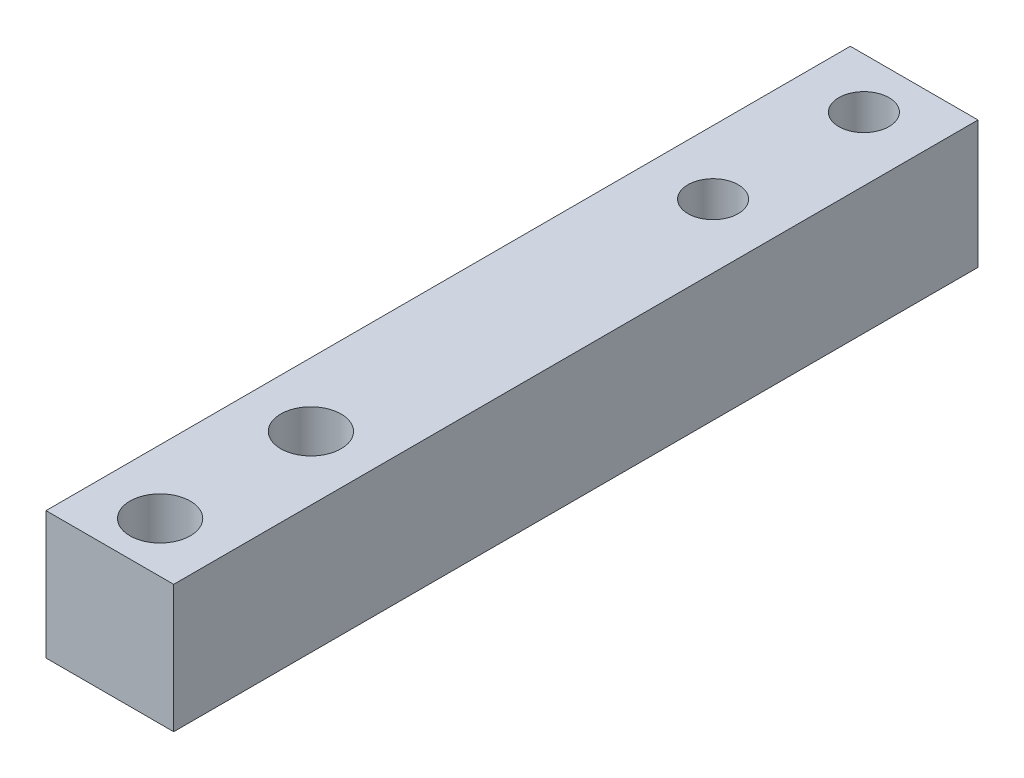
SolidWorks part; units mm, degrees
ref_plane "Front Plane" through (0, 0, 0) normal (0, 0, 1) x (1, 0, 0)
ref_plane "Top Plane" through (0, 0, 0) normal (0, 1, 0) x (1, 0, 0)
ref_plane "Right Plane" through (0, 0, 0) normal (1, 0, 0) x (0, 0, -1)
sketch "Sketch1" plane through (0, 0, 0) normal (0, 1, 0) x (1, 0, 0)
  line L0 (0, 40) -> (0, -40) construction
  line L1 (-6.35, 0) -> (6.35, 0) construction
  line L3 (-6.35, 40) -> (6.35, 40)
  line L4 (-6.35, 40) -> (-6.35, -40)
  line L5 (-6.35, -40) -> (6.35, -40)
  line L6 (6.35, 40) -> (6.35, -40)
  point P3 (0, 0)
  point P6 (0, 0)
  dimension "D1" = 80
  dimension "D2" = 12.7
extrude "Boss-Extrude1" add sketch "Sketch1" along normal blind 12.7
sketch "Sketch2" plane through (0, 12.7, 0) normal (0, 1, 0) x (1, 0, 0)
  line L0 (0, 40) -> (0, -40) construction
  circle A0 centre (0, 35) radius 2.5
  circle A1 centre (0, 20) radius 2.5
  circle A2 centre (0, -20) radius 3
  circle A3 centre (0, -35) radius 3
  point P10 (0, -29.9516)
  dimension "D5" = 5
  dimension "D6" = 5
  dimension "D7" = 6
  dimension "D8" = 6
  dimension "D1" = 40
  dimension "D2" = 20
  dimension "D3" = 15
  dimension "D4" = 15
extrude "Cut-Extrude1" cut sketch "Sketch2" against normal up to surface (12.7 mm away) up to face at (0, 0, 0)
